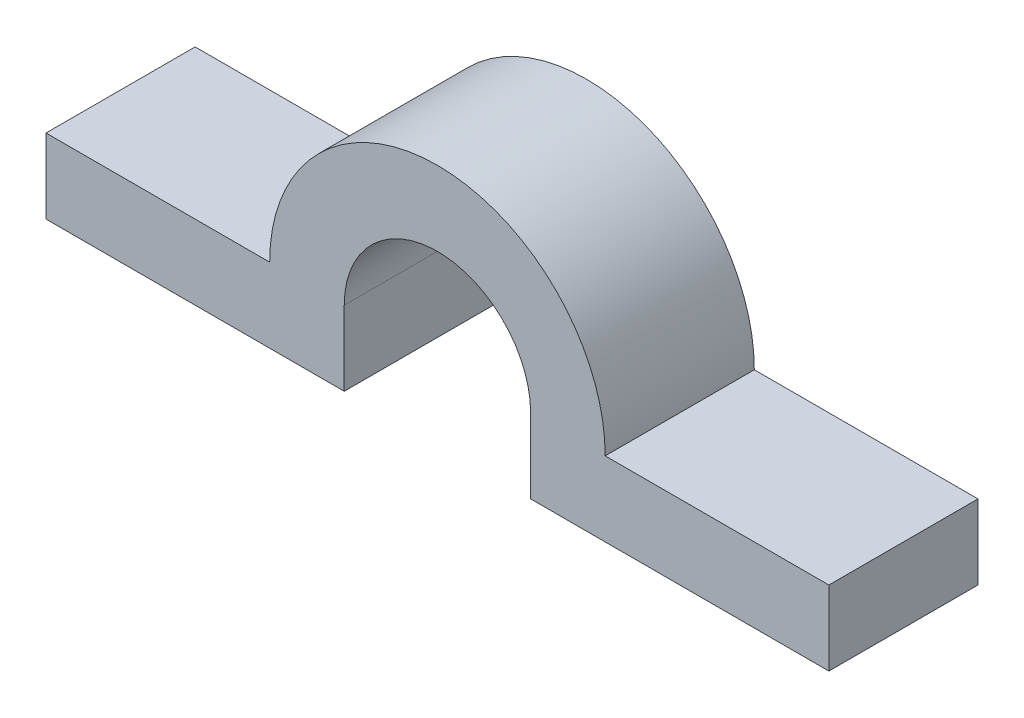
SolidWorks part; units mm, degrees
ref_plane "Front Plane" through (0, 0, 0) normal (0, 0, 1) x (1, 0, 0)
ref_plane "Top Plane" through (0, 0, 0) normal (0, 1, 0) x (1, 0, 0)
ref_plane "Right Plane" through (0, 0, 0) normal (1, 0, 0) x (0, 0, -1)
sketch "Sketch2" plane through (0, 0, 0) normal (0, 0, 1) x (1, 0, 0)
  line L4 (0, -4) -> (8, -4)
  line L6 (18, -4) -> (34, -4)
  line L7 (34, -4) -> (34, 0)
  line L8 (8, -4) -> (8, 0)
  line L9 (22, 0) -> (34, 0)
  line L10 (18, 0) -> (18, -4)
  line L12 (4, 0) -> (-8, 0)
  line L13 (-8, 0) -> (-8, -4)
  line L14 (-8, -4) -> (0, -4)
  arc A0 (18, 0) -> (8, 0) centre (13, 0) ccw
  arc A1 (22, 0) -> (4, 0) centre (13, 0) ccw
extrude "Boss-Extrude1" add sketch "Sketch2" along normal blind 8
